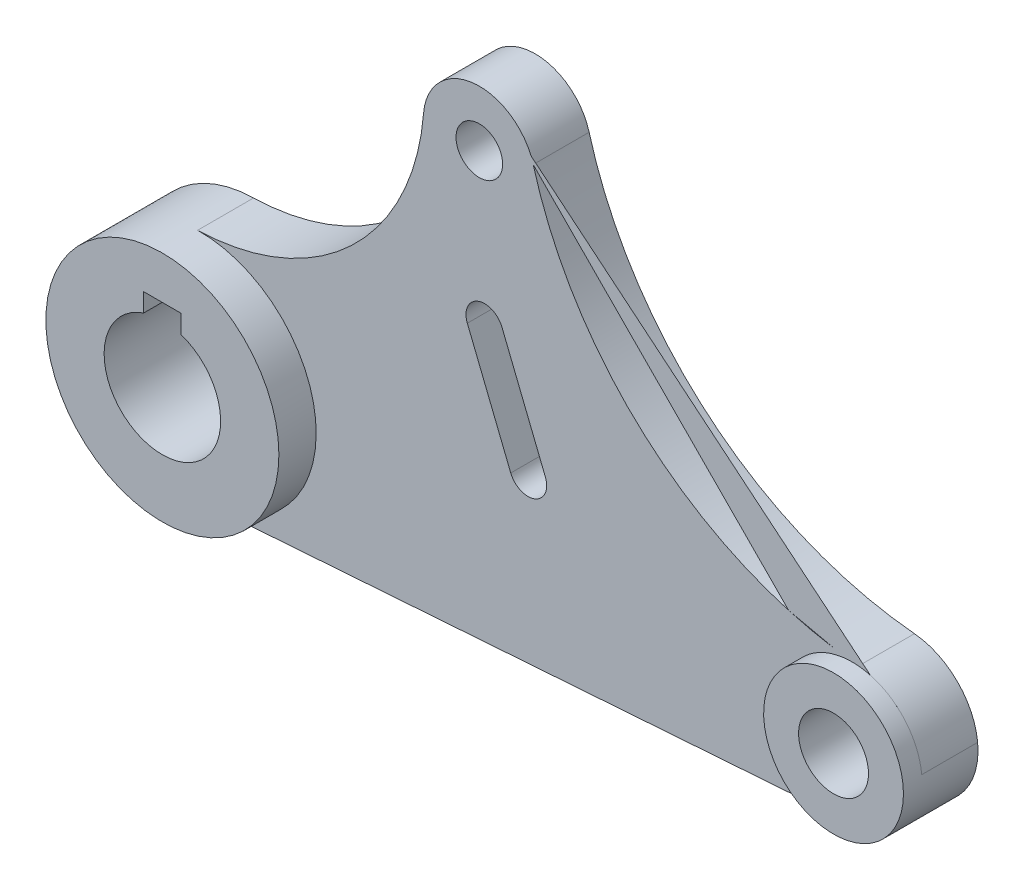
SolidWorks part; units mm, degrees
ref_plane "前视基准面" through (0, 0, 0) normal (0, 0, 1) x (1, 0, 0)
ref_plane "上视基准面" through (0, 0, 0) normal (0, 1, 0) x (1, 0, 0)
ref_plane "右视基准面" through (0, 0, 0) normal (1, 0, 0) x (0, 0, -1)
sketch "草图1" plane through (0, 0, 0) normal (0, 0, 1) x (1, 0, 0)
  line L0 (1.7857, -24.9362) -> (141.0714, -14.9617)
  arc A0 (141.0714, -14.9617) -> (141.3656, 14.9378) centre (139.9999, 0) ccw
  arc A1 (141.3656, 14.9378) -> (71.563, 73.209) centre (148.6499, 94.6072) cw
  arc A2 (71.563, 73.209) -> (48.039, 70.964) centre (60.0001, 70.0002) ccw
  arc A3 (48.039, 70.964) -> (-0.6, 24.992) centre (-1.8018, 74.9798) cw
  arc A4 (-0.6, 24.992) -> (1.7857, -24.9362) centre (0.0004, -0.0004) ccw
extrude "凸台-拉伸1" add sketch "草图1" along normal blind 12
sketch "草图2" plane through (0, 0, 0) normal (0, 0, 1) x (1, 0, 0)
  circle A0 centre (0, 0) radius 25
extrude "凸台-拉伸2" add sketch "草图2" along normal blind 20
sketch "草图3" plane through (0, 0, 0) normal (0, 0, 1) x (1, 0, 0)
  circle A0 centre (140, 0) radius 15
extrude "凸台-拉伸3" add sketch "草图3" along normal blind 16
sketch "草图4" plane through (0, 0, 0) normal (0, 0, 1) x (1, 0, 0)
  circle A0 centre (0, 0) radius 12.5
extrude "切除-拉伸1" cut sketch "草图4" along normal through all
sketch "草图5" plane through (0, 0, 0) normal (0, 0, 1) x (1, 0, 0)
  circle A0 centre (140, 0) radius 7.5
extrude "切除-拉伸2" cut sketch "草图5" along normal through all
sketch "草图6" plane through (0, 0, 0) normal (0, 0, 1) x (1, 0, 0)
  circle A0 centre (60, 70) radius 5
extrude "切除-拉伸3" cut sketch "草图6" along normal through all
sketch "草图7" plane through (0, 0, 0) normal (0, 0, 1) x (1, 0, 0)
  line L0 (-4, 0) -> (4, 0)
  line L1 (4, 0) -> (4, 15.8)
  line L2 (4, 15.8) -> (-4, 15.8)
  line L3 (-4, 15.8) -> (-4, 0)
extrude "切除-拉伸4" cut sketch "草图7" along normal through all
sketch "草图8" plane through (0, 0, 0) normal (0, 0, 1) x (1, 0, 0)
  line L0 (74.1686, 16.4688) -> (64.8539, 39.6446)
  line L1 (57.4309, 36.6612) -> (66.7456, 13.4854)
  arc A0 (64.8539, 39.6446) -> (57.4309, 36.6612) centre (61.1424, 38.1529) ccw
  arc A1 (66.7456, 13.4854) -> (74.1686, 16.4688) centre (70.4571, 14.9771) ccw
extrude "切除-拉伸5" cut sketch "草图8" along normal through all
